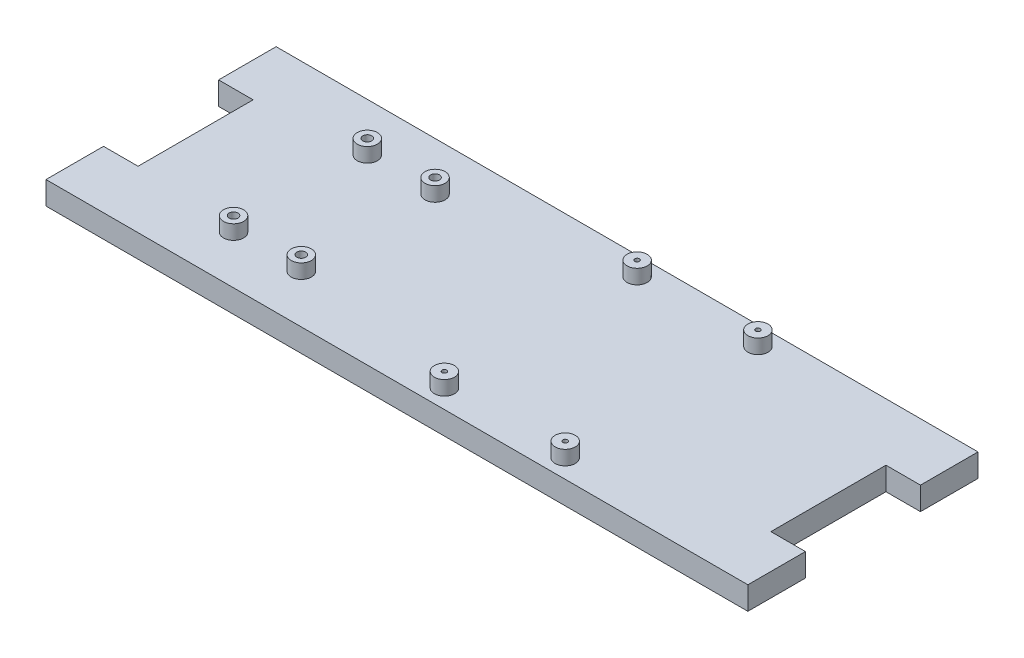
SolidWorks part; units mm, degrees
material "ABS"
ref_plane "Front Plane" through (0, 0, 0) normal (0, 0, 1) x (1, 0, 0)
ref_plane "Top Plane" through (0, 0, 0) normal (0, 1, 0) x (1, 0, 0)
ref_plane "Right Plane" through (0, 0, 0) normal (1, 0, 0) x (0, 0, -1)
sketch "Sketch2" plane through (0, 0, 0) normal (0, 1, 0) x (1, 0, 0)
  line L1 (-110, 40) -> (110, 40)
  line L2 (-110, 40) -> (-110, -40)
  line L3 (-110, -40) -> (110, -40)
  line L4 (110, 40) -> (110, -40)
  line L5 (-110, 40) -> (110, -40) construction
  line L6 (-110, -40) -> (110, 40) construction
  point P0 (0, 0)
  dimension "D1" = 220
  dimension "D2" = 80
extrude "Main" add sketch "Sketch2" along normal blind 8
sketch "Sketch3" plane through (110, 0, 0) normal (1, 0, 0) x (0, 0, -1)
  line L0 (-40, 0) -> (40, 0) construction
  line L1 (40, 8) -> (20, 8)
  line L2 (40, 8) -> (40, 0)
  line L3 (40, 0) -> (20, 0)
  line L4 (20, 8) -> (20, 0)
  dimension "D1" = 20
extrude "Tab" add sketch "Sketch3" along normal blind 12
mirror "Mirror1" about plane through (0, 0, 0) normal (1, 0, 0) of "Tab" second plane through (0, 0, 0) second plane normal (0, 0, 1)
sketch "Sketch4" plane through (0, 8, 0) normal (0, 1, 0) x (1, 0, 0)
  line L0 (10, 33.5) -> (52, 33.5) construction
  line L1 (10, 33.5) -> (10, -33.5) construction
  line L2 (10, -33.5) -> (52, -33.5) construction
  line L3 (52, 33.5) -> (52, -33.5) construction
  line L4 (10, 33.5) -> (52, -33.5) construction
  line L5 (10, -33.5) -> (52, 33.5) construction
  line L6 (-73.55, 23.25) -> (-50, 23.25) construction
  line L7 (-73.55, 23.25) -> (-73.55, -23.25) construction
  line L8 (-73.55, -23.25) -> (-50, -23.25) construction
  line L9 (-50, 23.25) -> (-50, -23.25) construction
  line L10 (-73.55, 23.25) -> (-50, -23.25) construction
  line L11 (-73.55, -23.25) -> (-50, 23.25) construction
  circle A0 centre (10, 33.5) radius 0.8
  circle A1 centre (52, 33.5) radius 0.8
  circle A2 centre (52, -33.5) radius 0.8
  circle A3 centre (10, -33.5) radius 0.8
  circle A4 centre (-73.55, 23.25) radius 1.55
  circle A5 centre (-50, 23.25) radius 1.55
  circle A6 centre (-50, -23.25) radius 1.55
  circle A7 centre (-73.55, -23.25) radius 1.55
  point P0 (31, 0)
  point P9 (-61.775, 0)
  dimension "D3" = 1.6
  dimension "D6" = 3.1
  dimension "D1" = 42
  dimension "D2" = 67
  dimension "D4" = 23.55
  dimension "D5" = 46.5
  dimension "D7" = 50
  dimension "D8" = 10
extrude "PCB holes" cut sketch "Sketch4" against normal through all
sketch "Sketch5" plane through (0, 8, 0) normal (0, 1, 0) x (1, 0, 0)
  circle A0 centre (-73.55, 23.25) radius 3.5
  circle A1 centre (-50, 23.25) radius 3.5
  circle A2 centre (-73.55, -23.25) radius 3.5
  circle A3 centre (-50, -23.25) radius 3.5
  circle A4 centre (10, -33.5) radius 3.5
  circle A5 centre (52, -33.5) radius 3.5
  circle A6 centre (52, 33.5) radius 3.5
  circle A7 centre (10, 33.5) radius 3.5
  circle A8 centre (10, 33.5) radius 0.8 construction
  circle A9 centre (52, 33.5) radius 0.8 construction
  circle A10 centre (52, -33.5) radius 0.8 construction
  circle A11 centre (10, -33.5) radius 0.8 construction
  circle A12 centre (-50, -23.25) radius 1.55 construction
  circle A13 centre (-73.55, -23.25) radius 1.55 construction
  circle A14 centre (-50, 23.25) radius 1.55 construction
  circle A15 centre (-73.55, 23.25) radius 1.55 construction
  circle A16 centre (10, 33.5) radius 0.8
  circle A17 centre (52, 33.5) radius 0.8
  circle A18 centre (52, -33.5) radius 0.8
  circle A19 centre (10, -33.5) radius 0.8
  circle A20 centre (-50, -23.25) radius 1.55
  circle A21 centre (-73.55, -23.25) radius 1.55
  circle A22 centre (-50, 23.25) radius 1.55
  circle A23 centre (-73.55, 23.25) radius 1.55
  dimension "D1" = 7
extrude "PCB pegs" add sketch "Sketch5" along normal blind 5
equation "\"length\" = 215mm"
equation "\"width\" = 220mm"
equation "\"height\" = 100mm"
equation "\"skin_th\" = 8mm"
equation "\"shelf_height\" = 10mm"
equation "\"D1@Sketch2\"=\"width\""
equation "\"D1@Main\"=\"skin_th\""
equation "\"D1@Tab\"=\"skin_th\" * 1.5"
